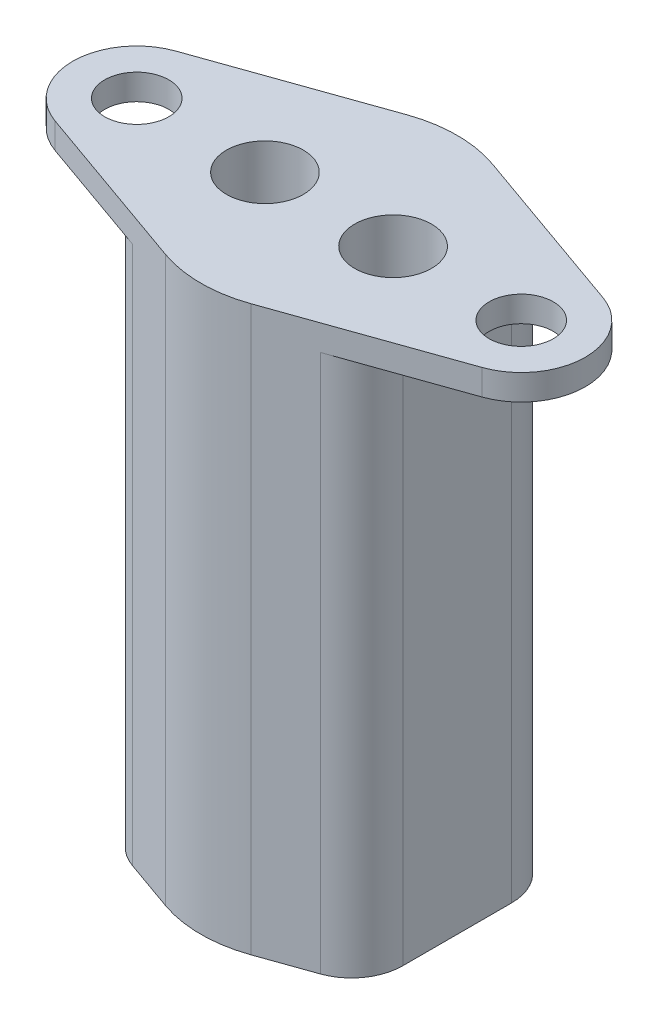
SolidWorks part; units mm, degrees
ref_plane "Front Plane" through (0, 0, 0) normal (0, 0, 1) x (1, 0, 0)
ref_plane "Top Plane" through (0, 0, 0) normal (0, 1, 0) x (1, 0, 0)
ref_plane "Right Plane" through (0, 0, 0) normal (1, 0, 0) x (0, 0, -1)
sketch "Sketch2" plane through (0, 0, 0) normal (0, 1, 0) x (1, 0, 0)
  line L0 (-7.5, 0) -> (7.5, 0) construction
  line L2 (-8.3333, -2.357) -> (-1.6667, -4.714)
  line L3 (1.6667, -4.714) -> (8.3333, -2.357)
  line L4 (1.6667, 4.714) -> (8.3333, 2.357)
  line L5 (-8.3333, 2.357) -> (-1.6667, 4.714)
  arc A0 (-1.6667, -4.714) -> (1.6667, -4.714) centre (0, 0) ccw
  arc A1 (-8.3333, 2.357) -> (-8.3333, -2.357) centre (-7.5, 0) ccw
  arc A2 (8.3333, -2.357) -> (8.3333, 2.357) centre (7.5, 0) ccw
  arc A3 (1.6667, 4.714) -> (-1.6667, 4.714) centre (0, 0) ccw
  circle A4 centre (-7.5, 0) radius 1.25
  circle A5 centre (7.5, 0) radius 1.25
  dimension "D1" = 10
  dimension "D2" = 5
  dimension "D3" = 5
  dimension "D5" = 2.5
  dimension "D6" = 2.5
  dimension "D4" = 15
extrude "Boss-Extrude1" add sketch "Sketch2" along normal blind 2
sketch "Sketch3" plane through (0, 0, 0) normal (0, 0, 1) x (1, 0, 0)
  line L0 (-10, 2) -> (-10, 0) construction
  line L1 (-10, 1) -> (-5, 1)
  line L2 (-10, 1) -> (-10, 0)
  line L3 (-10, 0) -> (-5, 0)
  line L4 (-5, 1) -> (-5, 0)
  line L5 (-8.3333, 0) -> (-1.6667, 0) construction
  line L6 (1.6667, 0) -> (8.3333, 0) construction
  line L7 (5, 0) -> (10, 0)
  line L8 (5, 0) -> (5, 1)
  line L9 (5, 1) -> (10, 1)
  line L10 (10, 0) -> (10, 1)
  line L11 (10, 0) -> (10, 2) construction
  dimension "D1" = 1
  dimension "D2" = 5
  dimension "D3" = 5
extrude "Cut-Extrude1" cut sketch "Sketch3" against normal through all both and the other way through all
fillet "Fillet1" radius 2 4 edges at (5, 0.5, 3.5355) (5, 0.5, -3.5355) (-5, 0.5, -3.5355) (-5, 0.5, 3.5355)
sketch "Sketch5" plane through (0, 0, 0) normal (0, -1, 0) x (1, 0, 0)
  line L6 (5, -2.1213) -> (5, 2.1213)
  line L7 (3.6667, 4.0069) -> (1.6667, 4.714)
  line L8 (-1.6667, 4.714) -> (-3.6667, 4.0069)
  line L9 (-5, 2.1213) -> (-5, -2.1213)
  line L10 (-3.6667, -4.0069) -> (-1.6667, -4.714)
  line L11 (1.6667, -4.714) -> (3.6667, -4.0069)
  line L12 (5, -2.1213) -> (5, 2.1213)
  line L13 (3.6667, 4.0069) -> (1.6667, 4.714)
  line L14 (-1.6667, 4.714) -> (-3.6667, 4.0069)
  line L15 (-5, 2.1213) -> (-5, -2.1213)
  line L16 (-3.6667, -4.0069) -> (-1.6667, -4.714)
  line L17 (1.6667, -4.714) -> (3.6667, -4.0069)
  arc A6 (5, 2.1213) -> (3.6667, 4.0069) centre (3, 2.1213) ccw
  arc A7 (1.6667, 4.714) -> (-1.6667, 4.714) centre (0, 0) ccw
  arc A8 (-3.6667, 4.0069) -> (-5, 2.1213) centre (-3, 2.1213) ccw
  arc A9 (-5, -2.1213) -> (-3.6667, -4.0069) centre (-3, -2.1213) ccw
  arc A10 (-1.6667, -4.714) -> (1.6667, -4.714) centre (0, 0) ccw
  arc A11 (3.6667, -4.0069) -> (5, -2.1213) centre (3, -2.1213) ccw
  arc A12 (5, 2.1213) -> (3.6667, 4.0069) centre (3, 2.1213) ccw
  arc A13 (1.6667, 4.714) -> (-1.6667, 4.714) centre (0, 0) ccw
  arc A14 (-3.6667, 4.0069) -> (-5, 2.1213) centre (-3, 2.1213) ccw
  arc A15 (-5, -2.1213) -> (-3.6667, -4.0069) centre (-3, -2.1213) ccw
  arc A16 (-1.6667, -4.714) -> (1.6667, -4.714) centre (0, 0) ccw
  arc A17 (3.6667, -4.0069) -> (5, -2.1213) centre (3, -2.1213) ccw
  dimension "D1" = 0
extrude "Boss-Extrude2" add sketch "Sketch5" along normal blind 20
sketch "Sketch6" plane through (0, -20, 0) normal (0, -1, 0) x (1, 0, 0)
  line L0 (-2.5, 0) -> (2.5, 0) construction
  circle A1 centre (-2.5, 0) radius 1.5
  circle A2 centre (2.5, 0) radius 1.5
  dimension "D1" = 3
  dimension "D2" = 3
  dimension "D3" = 5
extrude "Cut-Extrude2" cut sketch "Sketch6" against normal through all
